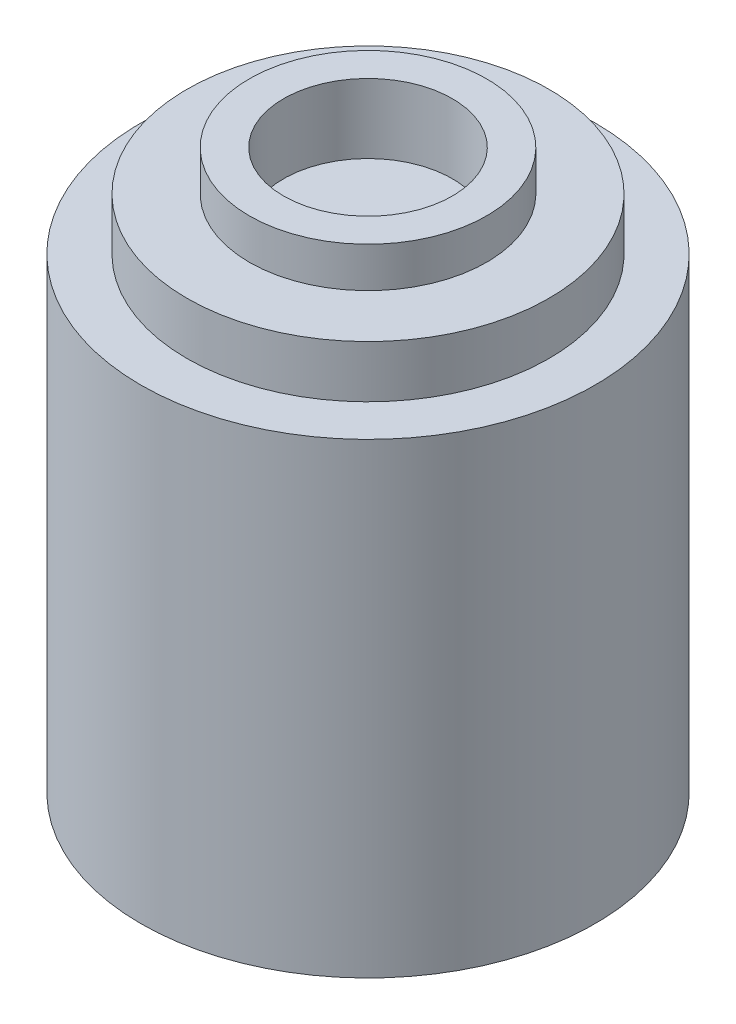
SolidWorks part; units mm, degrees
ref_plane "Front Plane" through (0, 0, 0) normal (0, 0, 1) x (1, 0, 0)
ref_plane "Top Plane" through (0, 0, 0) normal (0, 1, 0) x (1, 0, 0)
ref_plane "Right Plane" through (0, 0, 0) normal (1, 0, 0) x (0, 0, -1)
sketch "Эскиз1" plane through (0, 0, 0) normal (0, 1, 0) x (1, 0, 0)
  circle A0 centre (0, 0) radius 19.34
  circle A1 centre (0, 0) radius 15
  dimension "D1" = 38.68
  dimension "D2" = 30
ref_plane "Плоскость1" through (0, -11.3, 0) normal (0, 1, 0) x (1, 0, 0)
sketch "Эскиз2" plane through (0, -11.3, 0) normal (0, 1, 0) x (1, 0, 0)
  circle A0 centre (0, 0) radius 13.75
  dimension "D1" = 27.5
ref_plane "Плоскость2" through (0, -6.55, 0) normal (0, 1, 0) x (1, 0, 0)
sketch "Эскиз4" plane through (0, -6.55, 0) normal (0, 1, 0) x (1, 0, 0)
  circle A0 centre (0, 0) radius 29.5
  dimension "D1" = 59
ref_plane "Плоскость3" through (0, -15.05, 0) normal (0, 1, 0) x (1, 0, 0)
sketch "Эскиз5" plane through (0, -15.05, 0) normal (0, 1, 0) x (1, 0, 0)
  circle A0 centre (0, 0) radius 37
  dimension "D1" = 74
extrude "Бобышка-Вытянуть1" add sketch "Эскиз5" against normal blind 76
extrude "Бобышка-Вытянуть2" add sketch "Эскиз4" against normal up to body
extrude "Бобышка-Вытянуть3" add sketch "Эскиз1" against normal up to body contours A0
extrude "Вырез-Вытянуть1" cut sketch "Эскиз2" along normal up to surface (11.3 mm away) up to face at (0, 0, 19.34)
sketch "Эскиз6" plane through (0, 0, 0) normal (0, 0, 1) x (1, 0, 0)
  line L0 (0, 0) -> (0, 7.0797) construction
sketch "Эскиз7" plane through (0, -91.05, 0) normal (0, -1, 0) x (1, 0, 0)
  circle A0 centre (0, 0) radius 17
  circle A1 centre (0, 0) radius 35.5
  dimension "D1" = 71
  dimension "D2" = 34
extrude "Вырез-Вытянуть2" cut sketch "Эскиз7" against normal blind 9
